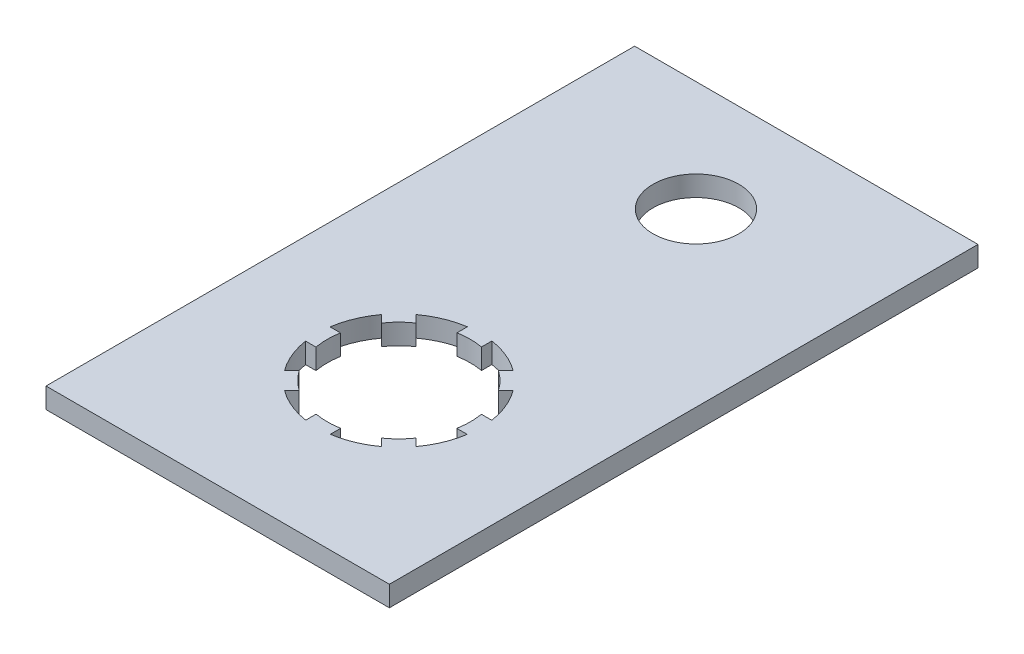
SolidWorks part; units mm, degrees
material "ABS"
ref_plane "Front Plane" through (0, 0, 0) normal (0, 0, 1) x (1, 0, 0)
ref_plane "Top Plane" through (0, 0, 0) normal (0, 1, 0) x (1, 0, 0)
ref_plane "Right Plane" through (0, 0, 0) normal (1, 0, 0) x (0, 0, -1)
sketch "Sketch1" plane through (0, 0, 0) normal (0, 1, 0) x (1, 0, 0)
  line L0 (2.5636, -3.4015) -> (3.0184, -2.9467)
  line L1 (-11.43, 19.05) -> (11.43, 19.05)
  line L2 (-11.43, 19.05) -> (-11.43, -19.05)
  line L3 (-11.43, -19.05) -> (11.43, -19.05)
  line L4 (11.43, 19.05) -> (11.43, -19.05)
  line L5 (-11.43, 19.05) -> (1.2681, -2.1135) construction
  line L6 (-11.43, -19.05) -> (-4.4317, -7.3862) construction
  line L12 (0, -2.5977) -> (0, -2.5877) construction
  line L33 (0.762, -2.6535) -> (0.762, -2.0101)
  line L37 (-1.2681, -2.1135) -> (11.43, 19.05) construction
  line L38 (4.431, -7.385) -> (11.43, -19.05) construction
  line L39 (-0.762, -2.6535) -> (-0.762, -2.0101)
  line L40 (-2.5636, -3.4015) -> (-3.0184, -2.9467)
  line L41 (0, 0) -> (0, 19.05) construction
  line L42 (-3.6395, -4.4808) -> (-4.0945, -4.0258)
  line L43 (-12.192, 19.812) -> (-12.192, -19.812)
  line L44 (-12.192, -19.812) -> (12.192, -19.812)
  line L45 (12.192, 19.812) -> (12.192, -19.812)
  line L46 (-12.192, 19.812) -> (12.192, 19.812)
  line L48 (0.762, -12.0552) -> (0.762, -11.4119)
  line L50 (-5.021, -7.8047) -> (-4.3774, -7.8047)
  line L53 (-10.668, 18.288) -> (-10.668, -18.288)
  line L54 (-10.668, -18.288) -> (10.668, -18.288)
  line L55 (10.668, 18.288) -> (10.668, -18.288)
  line L56 (-10.668, 18.288) -> (10.668, 18.288)
  line L58 (-0.762, -12.0552) -> (-0.762, -11.4119)
  line L60 (-5.024, -6.2807) -> (-4.3809, -6.2807)
  line L63 (-3.6354, -9.5904) -> (-4.0903, -10.0453)
  line L65 (-2.5577, -10.668) -> (-3.0126, -11.1229)
  line L68 (2.5577, -10.668) -> (3.0126, -11.1229)
  line L69 (3.6354, -9.5904) -> (4.0903, -10.0453)
  line L70 (4.3774, -7.8047) -> (5.021, -7.8047)
  line L71 (4.3809, -6.2807) -> (5.024, -6.2807)
  line L72 (3.6395, -4.4808) -> (4.0945, -4.0258)
  circle A0 centre (0, 11.43) radius 2.667
  arc A1 (-3.0126, -11.1229) -> (-0.762, -12.0552) centre (0, -7.0327) ccw
  arc A7 (4.431, -7.385) -> (4.4371, -7.2967) centre (0, -7.0327) ccw
  arc A10 (-5.021, -7.8047) -> (-4.0903, -10.0453) centre (0, -7.0327) ccw
  arc A11 (-4.0945, -4.0258) -> (-5.024, -6.2807) centre (0, -7.0327) ccw
  arc A12 (-0.762, -2.0101) -> (-3.0184, -2.9467) centre (0, -7.0327) ccw
  arc A13 (3.0184, -2.9467) -> (0.762, -2.0101) centre (0, -7.0327) ccw
  arc A14 (5.024, -6.2807) -> (4.0945, -4.0258) centre (0, -7.0327) ccw
  arc A15 (4.0903, -10.0453) -> (5.021, -7.8047) centre (0, -7.0327) ccw
  arc A16 (0.762, -12.0552) -> (3.0126, -11.1229) centre (0, -7.0327) ccw
  arc A17 (-4.4383, -6.7887) -> (-4.4371, -7.2967) centre (0, -7.0327) ccw
  arc A18 (-2.9637, -3.7199) -> (-3.3223, -4.0796) centre (0, -7.0327) ccw
  arc A19 (-3.3128, -9.9963) -> (-2.953, -10.355) centre (0, -7.0327) ccw
  arc A20 (-0.254, -11.4704) -> (0.254, -11.4704) centre (0, -7.0327) ccw
  arc A21 (2.953, -10.355) -> (3.3128, -9.9963) centre (0, -7.0327) ccw
  arc A22 (4.431, -7.385) -> (4.4383, -6.7887) centre (0, -7.0327) ccw
  arc A23 (3.3223, -4.0796) -> (2.9637, -3.7199) centre (0, -7.0327) ccw
  arc A24 (0.254, -2.5949) -> (-0.254, -2.5949) centre (0, -7.0327) ccw
  arc A25 (-4.3809, -6.2807) -> (-4.3774, -7.8047) centre (0, -7.0327) ccw
  arc A26 (-2.5636, -3.4015) -> (-3.6395, -4.4808) centre (0, -7.0327) ccw
  arc A27 (0.762, -2.6535) -> (-0.762, -2.6535) centre (0, -7.0327) ccw
  arc A28 (3.6395, -4.4808) -> (2.5636, -3.4015) centre (0, -7.0327) ccw
  arc A29 (4.3774, -7.8047) -> (4.3809, -6.2807) centre (0, -7.0327) ccw
  arc A30 (2.5577, -10.668) -> (3.6354, -9.5904) centre (0, -7.0327) ccw
  arc A31 (-0.762, -11.4119) -> (0.762, -11.4119) centre (0, -7.0327) ccw
  arc A32 (-3.6354, -9.5904) -> (-2.5577, -10.668) centre (0, -7.0327) ccw
  point P0 (0, 0)
  dimension "D3" = 5.334
  dimension "D5" = 10.16
  dimension "D1" = 22.86
  dimension "D2" = 38.1
  dimension "D4" = 7.62
  dimension "D6" = 0.762
  dimension "D7" = 0.762
extrude "Boss-Extrude1" add sketch "Sketch1" along normal blind 1.27
